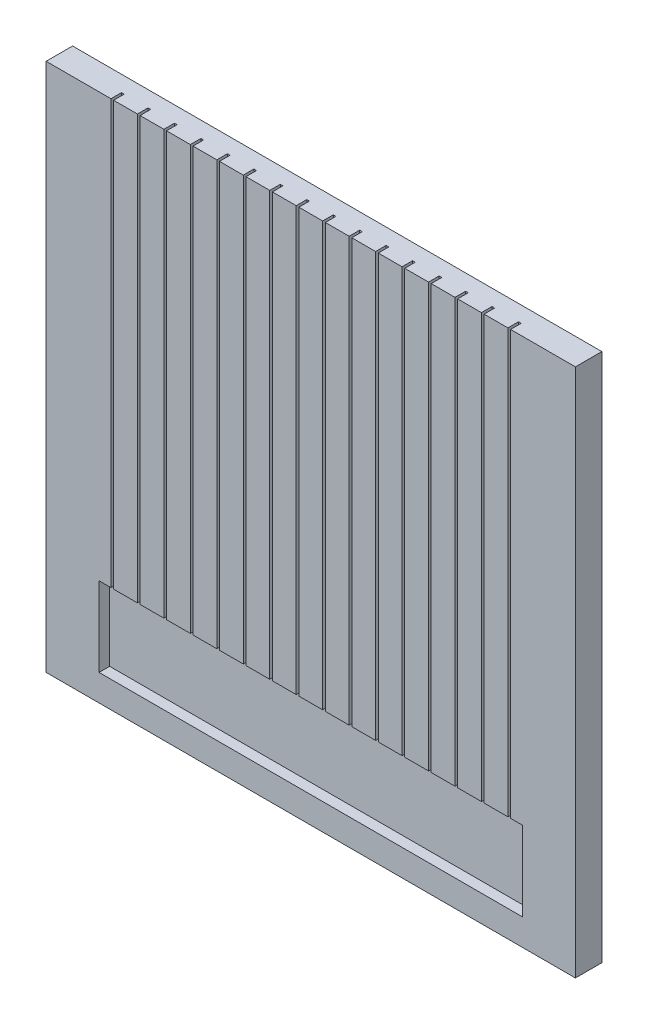
SolidWorks part; units mm, degrees
ref_plane "Front Plane" through (0, 0, 0) normal (1, 0, 0) x (0, 1, 0)
ref_plane "Top Plane" through (0, 0, 0) normal (0, 0, 1) x (0, 1, 0)
ref_plane "Right Plane" through (0, 0, 0) normal (0, 1, 0) x (-1, 0, 0)
sketch "Sketch1" plane through (0, 0, 0) normal (0, 0, 1) x (0, 1, 0)
  line L1 (0, 0) -> (10, 0)
  line L2 (0, 0) -> (0, -10)
  line L3 (0, -10) -> (10, -10)
  line L4 (10, 0) -> (10, -10)
  dimension "D1" = 10
  dimension "D2" = 10
extrude "Boss-Extrude1" add sketch "Sketch1" along normal blind 0.5
sketch "Sketch2" plane through (0, 0, 0.5) normal (0, 0, 1) x (1, 0, 0)
  line L0 (0, 10) -> (0, 0) construction
  line L1 (1, 0.5) -> (9, 0.5)
  line L2 (1, 0.5) -> (1, 2)
  line L3 (1, 2) -> (9, 2)
  line L4 (9, 0.5) -> (9, 2)
  line L5 (10, 0) -> (10, 10) construction
  line L6 (0, 0) -> (10, 0) construction
  dimension "D1" = 1
  dimension "D2" = 1
  dimension "D3" = 0.5
  dimension "D4" = 1.5
extrude "Cut-Extrude1" cut sketch "Sketch2" against normal blind 0.2
sketch "Sketch3" plane through (0, 0, 0.5) normal (0, 0, 1) x (1, 0, 0)
  line L0 (9, 2) -> (1, 2) construction
  line L1 (1.225, 2) -> (1.275, 2)
  line L2 (1.225, 2) -> (1.225, 10)
  line L3 (1.225, 10) -> (1.275, 10)
  line L4 (1.275, 2) -> (1.275, 10)
  line L5 (10, 10) -> (0, 10) construction
  line L6 (1.725, 2) -> (1.725, 10)
  line L7 (1.775, 2) -> (1.775, 10)
  line L8 (1.725, 2) -> (1.775, 2)
  line L9 (1.725, 10) -> (1.775, 10)
  line L10 (2.225, 2) -> (2.225, 10)
  line L11 (2.275, 2) -> (2.275, 10)
  line L12 (2.225, 2) -> (2.275, 2)
  line L13 (2.225, 10) -> (2.275, 10)
  line L14 (2.725, 2) -> (2.725, 10)
  line L15 (2.775, 2) -> (2.775, 10)
  line L16 (2.725, 2) -> (2.775, 2)
  line L17 (2.725, 10) -> (2.775, 10)
  line L18 (3.225, 2) -> (3.225, 10)
  line L19 (3.275, 2) -> (3.275, 10)
  line L20 (3.225, 2) -> (3.275, 2)
  line L21 (3.225, 10) -> (3.275, 10)
  line L22 (3.725, 2) -> (3.725, 10)
  line L23 (3.775, 2) -> (3.775, 10)
  line L24 (3.725, 2) -> (3.775, 2)
  line L25 (3.725, 10) -> (3.775, 10)
  line L26 (4.225, 2) -> (4.225, 10)
  line L27 (4.275, 2) -> (4.275, 10)
  line L28 (4.225, 2) -> (4.275, 2)
  line L29 (4.225, 10) -> (4.275, 10)
  line L30 (4.725, 2) -> (4.725, 10)
  line L31 (4.775, 2) -> (4.775, 10)
  line L32 (4.725, 2) -> (4.775, 2)
  line L33 (4.725, 10) -> (4.775, 10)
  line L34 (5.225, 2) -> (5.225, 10)
  line L35 (5.275, 2) -> (5.275, 10)
  line L36 (5.225, 2) -> (5.275, 2)
  line L37 (5.225, 10) -> (5.275, 10)
  line L38 (5.725, 2) -> (5.725, 10)
  line L39 (5.775, 2) -> (5.775, 10)
  line L40 (5.725, 2) -> (5.775, 2)
  line L41 (5.725, 10) -> (5.775, 10)
  line L42 (6.225, 2) -> (6.225, 10)
  line L43 (6.275, 2) -> (6.275, 10)
  line L44 (6.225, 2) -> (6.275, 2)
  line L45 (6.225, 10) -> (6.275, 10)
  line L46 (6.725, 2) -> (6.725, 10)
  line L47 (6.775, 2) -> (6.775, 10)
  line L48 (6.725, 2) -> (6.775, 2)
  line L49 (6.725, 10) -> (6.775, 10)
  line L50 (7.225, 2) -> (7.225, 10)
  line L51 (7.275, 2) -> (7.275, 10)
  line L52 (7.225, 2) -> (7.275, 2)
  line L53 (7.225, 10) -> (7.275, 10)
  line L54 (7.725, 2) -> (7.725, 10)
  line L55 (7.775, 2) -> (7.775, 10)
  line L56 (7.725, 2) -> (7.775, 2)
  line L57 (7.725, 10) -> (7.775, 10)
  line L58 (8.225, 2) -> (8.225, 10)
  line L59 (8.275, 2) -> (8.275, 10)
  line L60 (8.225, 2) -> (8.275, 2)
  line L61 (8.225, 10) -> (8.275, 10)
  line L62 (8.725, 2) -> (8.725, 10)
  line L63 (8.775, 2) -> (8.775, 10)
  line L64 (8.725, 2) -> (8.775, 2)
  line L65 (8.725, 10) -> (8.775, 10)
  line L66 (1, 2) -> (1.225, 2) construction
  line L67 (8.775, 2) -> (9, 2) construction
  dimension "D1" = 0.05
  dimension "D3" = 0.5
  dimension "D2" = 16
extrude "Cut-Extrude2" cut sketch "Sketch3" against normal blind 0.2
